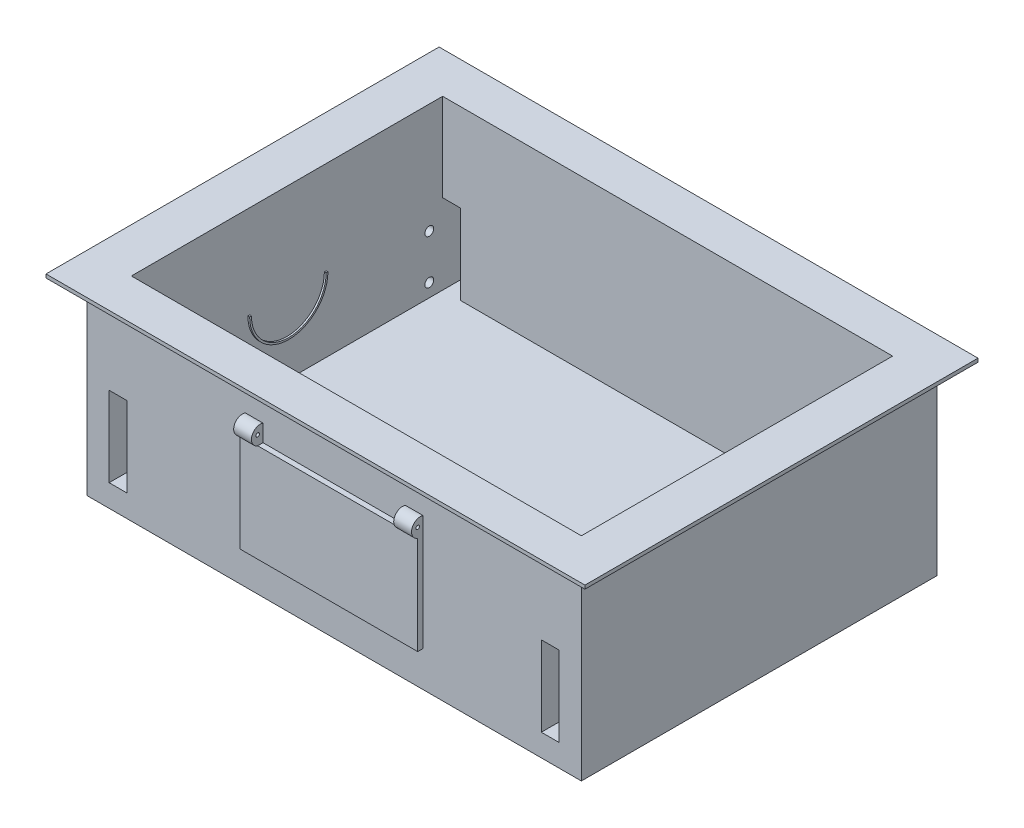
SolidWorks part; units mm, degrees
material "2195 Aluminum"
ref_plane "Front Plane" through (0, 0, 0) normal (0, 0, 1) x (1, 0, 0)
ref_plane "Top Plane" through (0, 0, 0) normal (0, 1, 0) x (1, 0, 0)
ref_plane "Right Plane" through (0, 0, 0) normal (1, 0, 0) x (0, 0, -1)
sketch "Sketch2" plane through (0, 0, 0) normal (0, 1, 0) x (1, 0, 0)
  line L0 (0, 437.5) -> (0, -437.5) construction
  line L1 (-632.5, 437.5) -> (632.5, 437.5)
  line L2 (-632.5, 437.5) -> (-632.5, -437.5)
  line L3 (-632.5, -437.5) -> (632.5, -437.5)
  line L4 (632.5, 437.5) -> (632.5, -437.5)
  line L5 (-632.5, 0) -> (632.5, 0) construction
  line L6 (-695, 48.7342) -> (-632.5, 48.7342) construction
  line L7 (-695, 500) -> (695, 500)
  line L8 (-695, 500) -> (-695, -500)
  line L9 (-695, -500) -> (695, -500)
  line L10 (695, 500) -> (695, -500)
  line L11 (632.5, 75.1796) -> (695, 75.1796) construction
  line L12 (-4.9015, 500) -> (-4.9015, 437.5) construction
  line L13 (-4.9015, -437.5) -> (-4.9015, -500) construction
  dimension "D1" = 62.5
  dimension "D2" = 1000
  dimension "D3" = 1390
extrude "Boss-Extrude1" add sketch "Sketch2" against normal blind 534.5
sketch "Sketch3" plane through (0, -534.5, 0) normal (0, -1, 0) x (1, 0, 0)
  line L0 (-695, 500) -> (-695, -500)
  line L3 (-695, 500) -> (695, 500)
  line L4 (695, -500) -> (695, 500)
  line L5 (-695, -500) -> (695, -500)
  line L6 (695, 500) -> (695, -500) construction
  line L7 (-695, 500) -> (695, 500) construction
  line L8 (-695, -500) -> (-695, 500) construction
  line L9 (695, -500) -> (-695, -500) construction
extrude "Boss-Extrude2" add sketch "Sketch3" against normal blind 62.5
sketch "Sketch4" plane through (695, 0, 0) normal (1, 0, 0) x (0, 0, -1)
  line L1 (0, 0) -> (0, -580.2055) construction
  line L2 (-105, -261) -> (-110, -261)
  line L3 (105, -261) -> (110, -261)
  arc A0 (-105, -261) -> (105, -261) centre (0, -261) ccw
  arc A1 (-110, -261) -> (110, -261) centre (0, -261) ccw
  dimension "D2" = 210
  dimension "D3" = 220
  dimension "D1" = 261
extrude "MMRTG Holder" add sketch "Sketch4" against normal blind 5 from offset 62.5 offset against normal yes
mirror "Mirror1" about plane through (0, 0, 0) normal (1, 0, 0) of "MMRTG Holder"
sketch "Sketch5" plane through (695, 0, 0) normal (1, 0, 0) x (0, 0, -1)
  line L0 (0, 70.8163) -> (0, -598.8061) construction
  line L1 (-500, -534.5) -> (500, -534.5) construction
  line L2 (-500, -534.5) -> (-500, 0) construction
  line L3 (-400, 39.1953) -> (-400, -618.3368) construction
  circle A0 centre (-400, -309.5) radius 12.5
  circle A1 centre (-400, -434.5) radius 12.5
  circle A2 centre (400, -434.5) radius 12.5
  circle A3 centre (400, -309.5) radius 12.5
  dimension "D4" = 25
  dimension "D1" = 125
  dimension "D2" = 100
  dimension "D3" = 100
extrude "Suspension Bolt Holes" cut sketch "Sketch5" against normal through all
sketch "Sketch6" plane through (0, 0, -500) normal (0, 0, -1) x (-1, 0, 0)
  line L0 (-695, -534.5) -> (-695, 0) construction
  line L1 (-632.5, -472) -> (-582.5, -472)
  line L2 (-632.5, -472) -> (-632.5, -247)
  line L3 (-632.5, -247) -> (-582.5, -247)
  line L4 (-582.5, -472) -> (-582.5, -247)
  line L5 (-695, -534.5) -> (695, -534.5) construction
  dimension "D1" = 62.5
  dimension "D2" = 62.5
  dimension "D3" = 50
  dimension "D4" = 225
extrude "Control Arm Cutout" cut sketch "Sketch6" against normal up to next
mirror "Mirror2" about plane through (0, 0, 0) normal (1, 0, 0) of "Control Arm Cutout"
mirror "Mirror3" about plane through (0, 0, 0) normal (0, 0, 1) of "Mirror2", "Control Arm Cutout"
sketch "Sketch7" plane through (0, 0, 0) normal (0, 1, 0) x (1, 0, 0)
  line L0 (695, 500) -> (-695, 500) construction
  line L1 (-757.5, 552.5) -> (757.5, 552.5)
  line L2 (-757.5, 552.5) -> (-757.5, -552.5)
  line L3 (-757.5, -552.5) -> (757.5, -552.5)
  line L4 (757.5, 552.5) -> (757.5, -552.5)
  line L5 (695, -500) -> (695, 500) construction
  line L7 (0, 552.5) -> (0, 500) construction
  line L8 (-632.5, 437.5) -> (632.5, 437.5)
  line L10 (0, -552.5) -> (0, -500) construction
  line L11 (-695, -500) -> (695, -500) construction
  line L12 (-632.5, 437.5) -> (-632.5, -437.5)
  line L13 (-632.5, -437.5) -> (632.5, -437.5)
  line L14 (632.5, 437.5) -> (632.5, -437.5)
  dimension "D1" = 52.5
  dimension "D2" = 62.5
  dimension "D3" = 52.5
extrude "AttachRoverFlange" add sketch "Sketch7" against normal blind 10
sketch "Sketch10" plane through (0, 0, 0) normal (0, 1, 0) x (1, 0, 0)
  line L0 (-726.25, 521.25) -> (-726.25, -475.2943) construction
  line L1 (-757.5, 552.5) -> (-757.5, -552.5) construction
  line L2 (757.5, 552.5) -> (-757.5, 552.5) construction
  line L3 (0, 0) -> (-1003.0581, 0) construction
  line L4 (-733.75, 0) -> (-718.75, 0)
  line L5 (0, 0) -> (0, 752.0536) construction
  line L6 (-726.25, 521.25) -> (0, 521.25) construction
  line L7 (0, 538.75) -> (0, 523.75)
  circle A0 centre (-726.25, 521.25) radius 7.5
  circle A1 centre (-726.25, 432.7083) radius 7.5
  circle A2 centre (-726.25, 344.1667) radius 7.5
  circle A3 centre (-726.25, 255.625) radius 7.5
  circle A4 centre (-635.4688, 521.25) radius 7.5
  circle A5 centre (-726.25, 167.0833) radius 7.5
  circle A6 centre (-726.25, 78.5417) radius 7.5
  circle A7 centre (-726.25, 0) radius 7.5
  circle A8 centre (-544.6875, 521.25) radius 7.5
  circle A9 centre (-453.9062, 521.25) radius 7.5
  circle A10 centre (-363.125, 521.25) radius 7.5
  circle A11 centre (-272.3438, 521.25) radius 7.5
  circle A12 centre (-181.5625, 521.25) radius 7.5
  circle A13 centre (0, 521.25) radius 7.5
  circle A14 centre (-90.7813, 521.25) radius 7.5
  circle A15 centre (90.7813, 521.25) radius 7.5
  circle A16 centre (181.5625, 521.25) radius 7.5
  circle A17 centre (272.3438, 521.25) radius 7.5
  circle A18 centre (363.125, 521.25) radius 7.5
  circle A19 centre (453.9062, 521.25) radius 7.5
  circle A20 centre (544.6875, 521.25) radius 7.5
  circle A21 centre (635.4688, 521.25) radius 7.5
  circle A22 centre (726.25, 521.25) radius 7.5
  circle A23 centre (726.25, 0) radius 7.5
  circle A24 centre (726.25, 78.5417) radius 7.5
  circle A25 centre (726.25, 167.0833) radius 7.5
  circle A26 centre (726.25, 255.625) radius 7.5
  circle A27 centre (726.25, 344.1667) radius 7.5
  circle A28 centre (726.25, 432.7083) radius 7.5
  circle A29 centre (726.25, -78.5417) radius 7.5
  circle A30 centre (726.25, -167.0833) radius 7.5
  circle A31 centre (726.25, -255.625) radius 7.5
  circle A32 centre (726.25, -344.1667) radius 7.5
  circle A33 centre (726.25, -432.7083) radius 7.5
  circle A34 centre (726.25, -521.25) radius 7.5
  circle A35 centre (635.4688, -521.25) radius 7.5
  circle A36 centre (544.6875, -521.25) radius 7.5
  circle A37 centre (453.9063, -521.25) radius 7.5
  circle A38 centre (363.125, -521.25) radius 7.5
  circle A39 centre (272.3438, -521.25) radius 7.5
  circle A40 centre (181.5625, -521.25) radius 7.5
  circle A41 centre (90.7813, -521.25) radius 7.5
  circle A42 centre (0, -521.25) radius 7.5
  circle A43 centre (-90.7812, -521.25) radius 7.5
  circle A44 centre (-181.5625, -521.25) radius 7.5
  circle A45 centre (-272.3437, -521.25) radius 7.5
  circle A46 centre (-363.125, -521.25) radius 7.5
  circle A47 centre (-453.9062, -521.25) radius 7.5
  circle A48 centre (-544.6875, -521.25) radius 7.5
  circle A49 centre (-635.4687, -521.25) radius 7.5
  circle A50 centre (-726.25, -521.25) radius 7.5
  circle A51 centre (-726.25, -344.1667) radius 7.5
  circle A52 centre (-726.25, -432.7083) radius 7.5
  circle A53 centre (-726.25, -255.625) radius 7.5
  circle A54 centre (-726.25, -167.0833) radius 7.5
  circle A55 centre (-726.25, -78.5417) radius 7.5
  dimension "D1" = 15
  dimension "D2" = 31.25
  dimension "D3" = 31.25
  dimension "D4" = 88.5417
  dimension "D5" = 88.5417
  dimension "D6" = 88.5417
  dimension "D7" = 88.5417
  dimension "D8" = 88.5417
  dimension "D9" = 90.7812
  dimension "D10" = 90.7812
  dimension "D11" = 90.7812
  dimension "D12" = 90.7812
  dimension "D13" = 90.7812
  dimension "D14" = 90.7812
  dimension "D15" = 90.7812
extrude "Attachment Holes" [suppressed] cut sketch "Sketch10" against normal up to next contours L4 A7 | L4 A7 | A6 | A5 | A3 | A2 | A1 | A0 | A4 | A8 | A9 | A10 | A11 | A12 | A14 | L7 A13 | L7 A13 | A15 | A16 | A17 | A18 | A19 | A20 | A21 | A22 | A28 | A27 | A26 | A25 | A24 | A23 | A29 | A30 | A31 | A32 | A33 | A34 | A35 | A36 | A39 | A38 | A37 | A42 | A41 | A40 | A43 | A44 | A45 | A46 | A47 | A48 | A49 | A50 | A52 | A51 | A55 | A54 | A53
sketch "Sketch11" plane through (695, 0, 0) normal (1, 0, 0) x (0, 0, -1)
  circle A0 centre (-400, -309.5) radius 12.5
  circle A1 centre (-400, -434.5) radius 12.5
  circle A2 centre (400, -309.5) radius 12.5
  circle A3 centre (400, -434.5) radius 12.5
  circle A4 centre (400, -309.5) radius 12.5 construction
  circle A5 centre (400, -434.5) radius 12.5 construction
  circle A6 centre (-400, -309.5) radius 12.5 construction
  circle A7 centre (-400, -434.5) radius 12.5 construction
extrude "Boss-Extrude3" add sketch "Sketch11" against normal blind 5
mirror "Mirror4" about plane through (0, 0, 0) normal (1, 0, 0) of "Boss-Extrude3"
sketch "Sketch13" plane through (0, 0, 0) normal (1, 0, 0) x (0, 0, -1)
  line L0 (500, -434.5) -> (500, -134.5)
  line L1 (500, -134.5) -> (515, -134.5)
  line L2 (515, -134.5) -> (515, -434.5)
  line L3 (515, -434.5) -> (500, -434.5)
  line L4 (500, -534.5) -> (500, -10) construction
  line L5 (-500, -534.5) -> (500, -534.5) construction
  circle A0 centre (507.5, -134.5) radius 25
  dimension "D1" = 50
  dimension "D2" = 15
  dimension "D3" = 100
  dimension "D4" = 300
extrude "Boss-Extrude4" add sketch "Sketch13" along normal blind 250 and the other way blind 250 contours L0 A0 L2 L1 | L2 A0 L0 L1
sketch "Sketch14" plane through (0, 0, -515) normal (0, 0, -1) x (-1, 0, 0)
  line L0 (-250, -158.3485) -> (250, -158.3485) construction
  line L1 (-200, -158.3485) -> (200, -158.3485)
  line L2 (-200, -158.3485) -> (-200, -102.8156)
  line L3 (-200, -102.8156) -> (200, -102.8156)
  line L4 (200, -158.3485) -> (200, -102.8156)
  line M5 (250, -158.3485) -> (-250, -158.3485)
  dimension "D1" = 400
  dimension "D2" = 200
extrude "Cut-Extrude1" cut sketch "Sketch14" along direction (0, 0, -1) on the side against the normal up to surface (15 mm away) and the other way blind 250 contours L4 L3 L2 M5
sketch "Sketch15" plane through (250, 0, 0) normal (1, 0, 0) x (0, 0, -1)
  line L0 (515, -179.502) -> (515, -132.0904) construction
  line L1 (515, -158.3485) -> (515, -434.5) construction
  circle A0 centre (515, -132.0904) radius 5
  point P0 (515, -132.0904)
  point P6 (515, -130.6537)
  point P7 (515, -131.6115)
  dimension "D1" = 10
extrude "Cut-Extrude2" cut sketch "Sketch15" against normal up to surface (500 mm away)
mirror "Mirror6" about plane through (0, 0, 0) normal (0, 0, 1) of "Boss-Extrude4", "Cut-Extrude2"
sketch "Sketch16" plane through (0, 0, 500) normal (0, 0, 1) x (1, 0, 0)
  line L0 (-250, -158.3485) -> (250, -158.3485) construction
  line L1 (-200, -91.606) -> (200, -91.606)
  line L2 (-200, -91.606) -> (-200, -158.3485)
  line L3 (-200, -158.3485) -> (200, -158.3485)
  line L4 (200, -91.606) -> (200, -158.3485)
  point P4 (177.9418, -164.4717)
  dimension "D1" = 400
  dimension "D2" = 200
extrude "Cut-Extrude3" cut sketch "Sketch16" along normal blind 607
equation "\"D3@Sketch2\"=1140+(4*(62.5))"
equation "\"D1@Boss-Extrude1\"=422+62.5+50"
equation "\"D4@Sketch10\"=531.25/6"
equation "\"D5@Sketch10\"=531.25/6"
equation "\"D6@Sketch10\"=531.25/6"
equation "\"D7@Sketch10\"=531.25/6"
equation "\"D8@Sketch10\"=531.25/6"
equation "\"D9@Sketch10\"=726.25/8"
equation "\"D10@Sketch10\"=726.25/8"
equation "\"D11@Sketch10\"=726.25/8"
equation "\"D12@Sketch10\"=726.25/8"
equation "\"D13@Sketch10\"=726.25/8"
equation "\"D14@Sketch10\"=726.25/8"
equation "\"D15@Sketch10\"=726.25/8"
